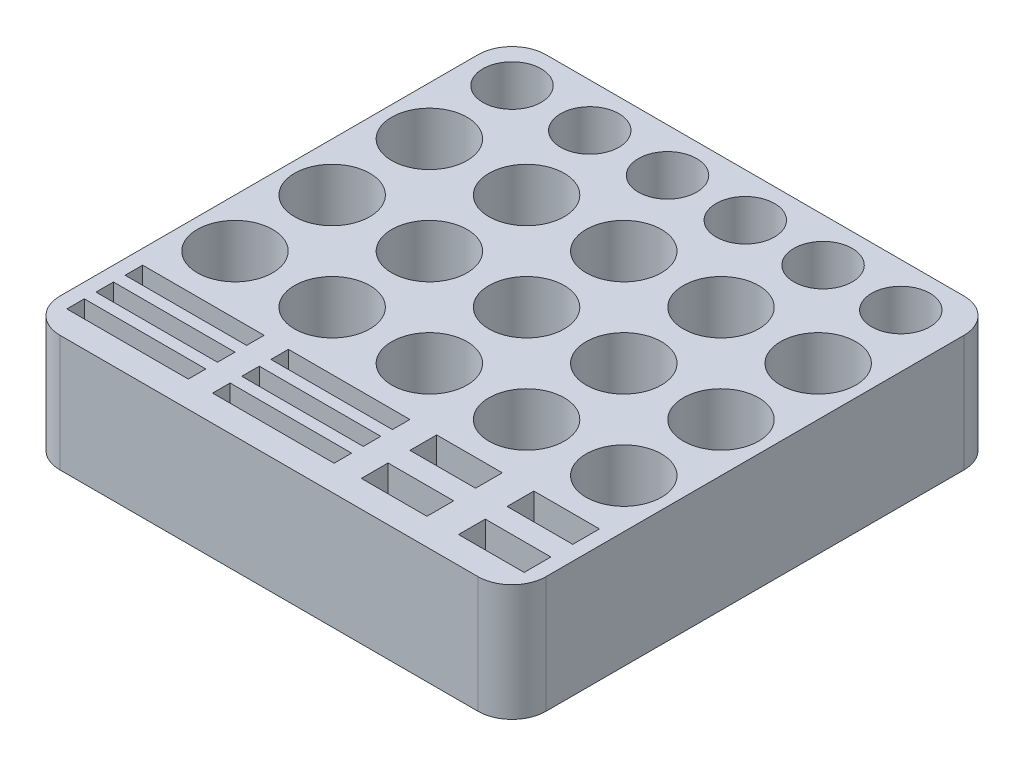
SolidWorks part; units mm, degrees
ref_plane "Front Plane" through (0, 0, 0) normal (0, 0, 1) x (1, 0, 0)
ref_plane "Top Plane" through (0, 0, 0) normal (0, 1, 0) x (1, 0, 0)
ref_plane "Right Plane" through (0, 0, 0) normal (1, 0, 0) x (0, 0, -1)
sketch "Sketch1" plane through (0, 0, 0) normal (0, 1, 0) x (1, 0, 0)
  line L1 (-50, -50) -> (50, -50)
  line L2 (-50, -50) -> (-50, 50)
  line L3 (-50, 50) -> (50, 50)
  line L4 (50, -50) -> (50, 50)
  line L5 (-50, -50) -> (50, 50) construction
  line L6 (-50, 50) -> (50, -50) construction
  point P0 (0, 0)
  dimension "D1" = 100
  dimension "D2" = 100
extrude "Boss-Extrude1" add sketch "Sketch1" along normal blind 24
sketch "Sketch2" plane through (0, 24, 0) normal (0, 1, 0) x (1, 0, 0)
  line L0 (0, 50) -> (0, -50) construction
  line L1 (50, 50) -> (-50, 50) construction
  line L2 (-50, -50) -> (50, -50) construction
  line L3 (-50, 0) -> (50, 0) construction
  line L4 (-50, 50) -> (-50, -50) construction
  line L5 (50, -50) -> (50, 50) construction
  line L6 (-17, -32.6) -> (8, -32.6)
  line L7 (-47, -32.6) -> (-22, -32.6)
  line L8 (-47, -32.6) -> (-47, -29)
  line L9 (-47, -29) -> (-22, -29)
  line L10 (-22, -32.6) -> (-22, -29)
  line L11 (-47, -32.6) -> (-22, -29) construction
  line L12 (-47, -29) -> (-22, -32.6) construction
  line L13 (-17, -32.6) -> (-17, -29)
  line L14 (-17, -29) -> (8, -29)
  line L15 (8, -32.6) -> (8, -29)
  line L16 (-17, -38.6) -> (8, -38.6)
  line L17 (-17, -38.6) -> (-17, -35)
  line L18 (-17, -35) -> (8, -35)
  line L19 (8, -38.6) -> (8, -35)
  line L20 (-17, -44.6) -> (8, -44.6)
  line L21 (-17, -44.6) -> (-17, -41)
  line L22 (-17, -41) -> (8, -41)
  line L23 (8, -44.6) -> (8, -41)
  line L24 (-47, -38.6) -> (-22, -38.6)
  line L25 (-47, -38.6) -> (-47, -35)
  line L26 (-47, -35) -> (-22, -35)
  line L27 (-22, -38.6) -> (-22, -35)
  line L28 (-47, -44.6) -> (-22, -44.6)
  line L29 (-47, -44.6) -> (-47, -41)
  line L30 (-47, -41) -> (-22, -41)
  line L31 (-22, -44.6) -> (-22, -41)
  line L32 (27, -34.5) -> (27, -29)
  line L33 (33.5, -34.5) -> (47, -34.5)
  line L34 (33.5, -34.5) -> (33.5, -29)
  line L35 (33.5, -29) -> (47, -29)
  line L36 (47, -34.5) -> (47, -29)
  line L37 (33.5, -34.5) -> (47, -29) construction
  line L38 (33.5, -29) -> (47, -34.5) construction
  line L39 (13.5, -29) -> (27, -29)
  line L40 (13.5, -34.5) -> (27, -34.5)
  line L41 (13.5, -34.5) -> (13.5, -29)
  line L42 (27, -44.5) -> (27, -39)
  line L43 (13.5, -39) -> (27, -39)
  line L44 (13.5, -44.5) -> (27, -44.5)
  line L45 (13.5, -44.5) -> (13.5, -39)
  line L46 (47, -44.5) -> (47, -39)
  line L47 (33.5, -39) -> (47, -39)
  line L48 (33.5, -44.5) -> (47, -44.5)
  line L49 (33.5, -44.5) -> (33.5, -39)
  circle A0 centre (-41, 41) radius 6
  circle A1 centre (-25, 41) radius 6
  circle A2 centre (-9, 41) radius 6
  circle A3 centre (7, 41) radius 6
  circle A4 centre (23, 41) radius 6
  circle A5 centre (39, 41) radius 6
  circle A6 centre (-40, 23) radius 7.75
  circle A7 centre (-20, 23) radius 7.75
  circle A8 centre (0, 23) radius 7.75
  circle A9 centre (20, 23) radius 7.75
  circle A10 centre (40, 23) radius 7.75
  circle A11 centre (-20, 3) radius 7.75
  circle A12 centre (0, 3) radius 7.75
  circle A13 centre (20, 3) radius 7.75
  circle A14 centre (40, 3) radius 7.75
  circle A15 centre (-20, -17) radius 7.75
  circle A16 centre (0, -17) radius 7.75
  circle A17 centre (20, -17) radius 7.75
  circle A18 centre (40, -17) radius 7.75
  circle A19 centre (-40, 3) radius 7.75
  circle A20 centre (-40, -17) radius 7.75
  point P26 (-34.5, -30.8)
  point P59 (40.25, -31.75)
  dimension "D1" = 12
  dimension "D5" = 15.5
  dimension "D2" = 9
  dimension "D3" = 9
  dimension "D6" = 10
  dimension "D7" = 18
  dimension "D10" = 25
  dimension "D11" = 3.6
  dimension "D12" = 12
  dimension "D13" = 3
  dimension "D16" = 5.5
  dimension "D17" = 13.5
  dimension "D18" = 3
  dimension "D19" = 12
  dimension "D4" = 6
  dimension "D8" = 5
  dimension "D9" = 3
  dimension "D14" = 2
  dimension "D15" = 3
  dimension "D20" = 2
  dimension "D21" = 2
extrude "Cut-Extrude1" cut sketch "Sketch2" against normal blind 22
fillet "Fillet1" radius 7 4 edges at (-50, 12, -50) (50, 12, -50) (50, 12, 50) (-50, 12, 50)
